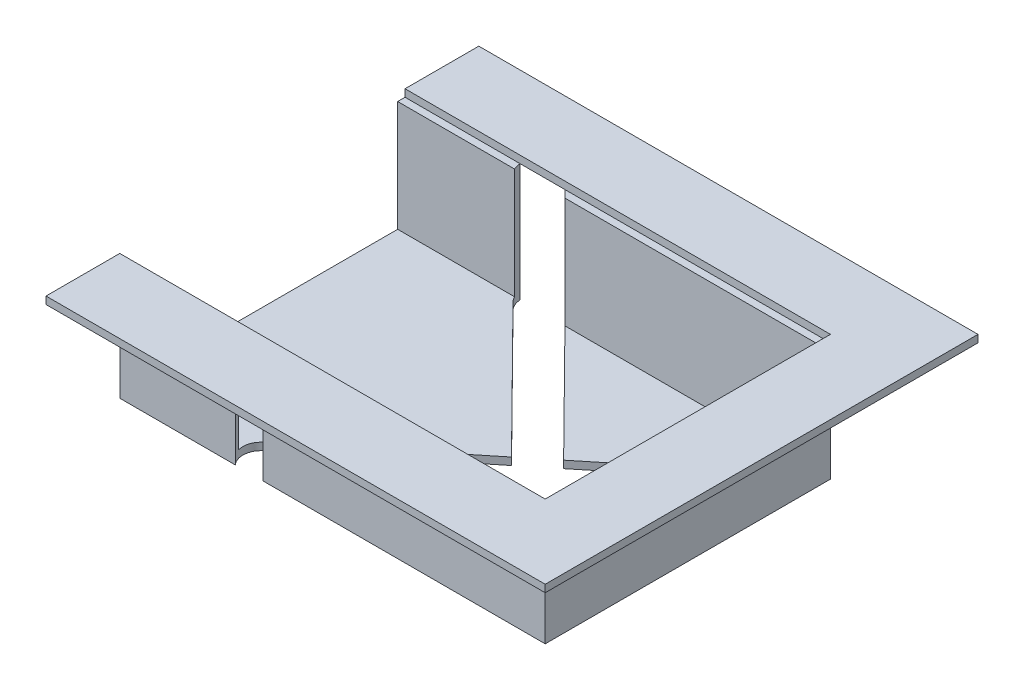
SolidWorks part; units mm, degrees
ref_plane "Alzado" through (0, 0, 0) normal (0, 0, 1) x (1, 0, 0)
ref_plane "Planta" through (0, 0, 0) normal (0, 1, 0) x (1, 0, 0)
ref_plane "Vista lateral" through (0, 0, 0) normal (1, 0, 0) x (0, 0, -1)
sketch "Sketch1" plane through (0, 0, 0) normal (0, 1, 0) x (1, 0, 0)
  line L1 (-13.0164, -14.3358) -> (162.9836, -14.3358)
  line L2 (-13.0164, -14.3358) -> (-13.0164, 101.6642)
  line L3 (-13.0164, 101.6642) -> (162.9836, 101.6642)
  line L4 (162.9836, -14.3358) -> (162.9836, 101.6642)
  dimension "D1" = 116
  dimension "D2" = 176
extrude "Boss-Extrude1" add sketch "Sketch1" along normal blind 48
shell "Shell1" thickness 3
sketch "Sketch2" plane through (0, 48, 0) normal (0, 1, 0) x (1, 0, 0)
  line L0 (-43.0164, -44.3358) -> (192.9836, -44.3358)
  line L1 (192.9836, -44.3358) -> (192.9836, 131.6642)
  line L2 (192.9836, 131.6642) -> (-43.0164, 131.6642)
  line L3 (-43.0164, 131.6642) -> (-43.0164, -44.3358)
  line L4 (-13.0164, 101.6642) -> (-13.0164, -14.3358)
  line L5 (-13.0164, -14.3358) -> (162.9836, -14.3358)
  line L6 (162.9836, -14.3358) -> (162.9836, 101.6642)
  line L7 (162.9836, 101.6642) -> (-13.0164, 101.6642)
  line L8 (-13.0164, 101.6642) -> (-13.0164, -14.3358)
  line L9 (-13.0164, -14.3358) -> (162.9836, -14.3358)
  line L10 (162.9836, -14.3358) -> (162.9836, 101.6642)
  line L11 (162.9836, 101.6642) -> (-13.0164, 101.6642)
  dimension "D1" = 0
  dimension "D2" = 30
extrude "Boss-Extrude2" add sketch "Sketch2" along normal blind 3 separate body
sketch "Sketch5" plane through (0, 51, 0) normal (0, 1, 0) x (1, 0, 0)
  line L0 (-10.0164, -51.3358) -> (-10.0164, 131.6642)
  line L1 (-10.0164, 131.6642) -> (-43.0164, 131.6642)
  line L2 (-43.0164, 131.6642) -> (-43.0164, -84.3358)
  line L3 (-43.0164, -84.3358) -> (-10.0164, -84.3358)
  line L4 (-10.0164, -84.3358) -> (-10.0164, -51.3358)
extrude "Cut-Extrude1" cut sketch "Sketch5" against normal through all
sketch "Sketch6" plane through (0, 0, 0) normal (0, -1, 0) x (1, 0, 0)
  line L0 (42.5362, 9.3243) -> (71.57, -14.2657) construction
  line L1 (71.57, -14.2657) -> (143.431, -72.6528) construction
  line L2 (135.6854, -9.4436) -> (44.2818, -101.8849) construction
  line L3 (42.5362, 9.3243) -> (143.431, -72.6528) construction
  line L4 (47.2656, 15.1451) -> (148.1605, -66.8319)
  line L5 (37.8067, 3.5034) -> (138.7016, -78.4736)
  line L6 (135.6854, -9.4436) -> (44.2818, -101.8849) construction
  line L7 (141.0185, -14.7169) -> (49.615, -107.1582)
  line L8 (130.3522, -4.1703) -> (38.9487, -96.6116)
  line L9 (-10.0164, 14.3358) -> (-10.0164, -101.6642) construction
  line L11 (-10.0164, 44.3358) -> (192.9836, 44.3358) construction
  line L12 (192.9836, -131.6642) -> (-10.0164, -131.6642) construction
  line L13 (192.9836, 44.3358) -> (192.9836, -131.6642) construction
  arc A1 (47.2656, 15.1451) -> (37.8067, 3.5034) centre (42.5362, 9.3243) ccw
  arc A2 (138.7016, -78.4736) -> (148.1605, -66.8319) centre (143.431, -72.6528) ccw
  arc A3 (141.0185, -14.7169) -> (130.3522, -4.1703) centre (135.6854, -9.4436) ccw
  arc A4 (38.9487, -96.6116) -> (49.615, -107.1582) centre (44.2818, -101.8849) ccw
  point P1 (92.9836, -31.6642)
  point P10 (89.9836, -55.6642)
  point P15 (74.2448, -15.9521)
  point P20 (28.4259, -131.6642)
  dimension "D1" = 15
  dimension "D2" = 15
  dimension "D3" = 100
  dimension "D4" = 100
  dimension "D5" = 100
  dimension "D6" = 100
  dimension "D7" = 130
  dimension "D8" = 130
extrude "Cut-Extrude2" cut sketch "Sketch6" against normal through all contours L4 A2 L5 A1 | L8 A4 L7 A3
